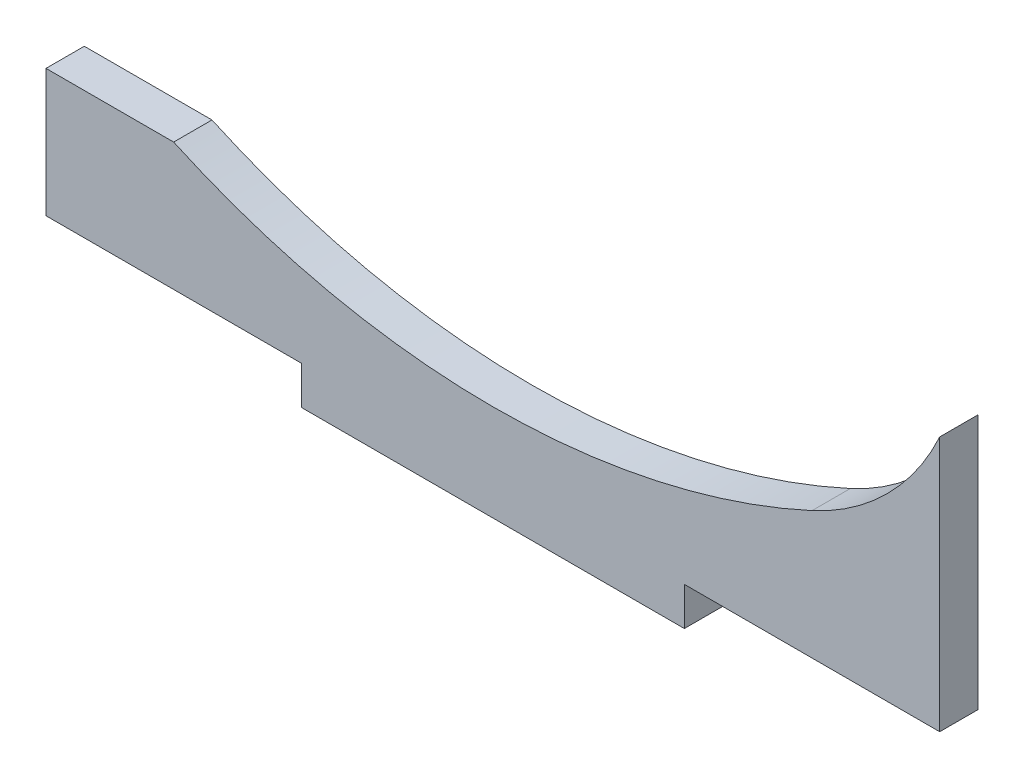
SolidWorks part; units mm, degrees
ref_plane "Front Plane" through (0, 0, 0) normal (0, 0, 1) x (1, 0, 0)
ref_plane "Top Plane" through (0, 0, 0) normal (0, 1, 0) x (1, 0, 0)
ref_plane "Right Plane" through (0, 0, 0) normal (1, 0, 0) x (0, 0, -1)
sketch "Sketch1" plane through (0, 0, 0) normal (0, 0, 1) x (1, 0, 0)
  line L0 (0, 0) -> (-20, 0)
  line L1 (-20, 0) -> (-20, -3)
  line L2 (-20, -3) -> (-50, -3)
  line L3 (-50, -3) -> (-50, 0)
  line L4 (-50, 0) -> (-70, 0)
  line L5 (-70, 0) -> (-70, 10)
  line L6 (-70, 10) -> (-60, 10)
  line L7 (0, 0) -> (0, 20)
  line L9 (0, 80) -> (0, -3) construction
  arc A1 (-10, 10) -> (-60, 10) centre (-35, 64.5436) cw
  arc A3 (-10, 10) -> (-10, 70) centre (-84.162, 40) ccw construction
  arc A4 (-10, 10) -> (0, 20) centre (-18.4621, 28.4621) ccw
  point P3 (-0.3957, 21.088)
  point P17 (0, 17.9564)
  dimension "D8" = 60
  dimension "D1" = 30
  dimension "D2" = 20
  dimension "D3" = 20
  dimension "D4" = 3
  dimension "D5" = 10
  dimension "D6" = 20
  dimension "D7" = 10
extrude "Boss-Extrude1" add sketch "Sketch1" along normal blind 3
